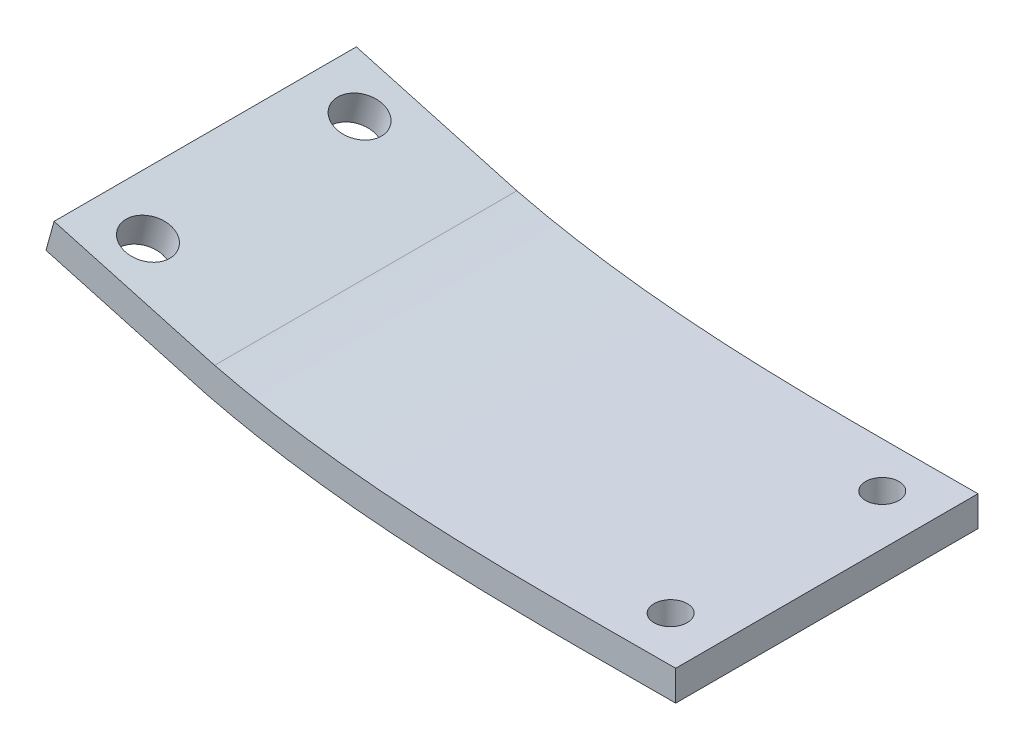
SolidWorks part; units mm, degrees
ref_plane "Piano frontale" through (0, 0, 0) normal (0, 0, 1) x (1, 0, 0)
ref_plane "Piano superiore" through (0, 0, 0) normal (0, 1, 0) x (1, 0, 0)
ref_plane "Piano destro" through (0, 0, 0) normal (1, 0, 0) x (0, 0, -1)
sketch "Schizzo1" plane through (0, 0, 0) normal (0, 0, 1) x (1, 0, 0)
  line L0 (0, 0) -> (150, 0)
  line L1 (150, 0) -> (94.2149, 0.9737) construction
  line L2 (150, 0) -> (78.851, 2.4846) construction
  line L3 (150, 0) -> (66.9131, 4.3544) construction
  line L4 (150, 0) -> (56.9541, 6.5064) construction
  line L5 (150, 0) -> (25.0148, 15.3463) construction
  line L6 (-299.0536, -537.5076) -> (-1111.2465, -622.8725) construction
  line L7 (25.0148, 15.3463) -> (56.9541, 6.5064)
  line L8 (26.6152, 21.1289) -> (58.4735, 12.3114)
  line L9 (149.9926, 6) -> (150, 0)
  line L10 (25.0148, 15.3463) -> (26.6152, 21.1289)
  spline S0 degree 3 poles (150, 0) (126.3707, -0.029) (94.9081, -0.7051) (64.164, 4.725) (56.9541, 6.5064) knots 0 0 0 0 0.761804 1 1 1 1
  spline S1 degree 1 poles (149.9926, 6) (58.4735, 12.3114) knots 0 0 1 1 construction
  spline S2 degree 3 poles (58.4735, 12.3114) (62.1265, 11.4109) (69.481, 9.8709) (84.4753, 7.647) (103.508, 6.2193) (126.6665, 5.8672) (142.2274, 5.9905) (149.9926, 6) knots 0 0 0 0 0.124885 0.249771 0.499542 0.749313 0.999084 0.999084 0.999084 0.999084
  dimension "D1" = 150
  dimension "D2" = 1
  dimension "D3" = 1
  dimension "D4" = 1
  dimension "D5" = 1
  dimension "D6" = 3
  dimension "D7" = 10.1888
  dimension "D8" = 12.0835
  dimension "D9" = 15.438
  dimension "D10" = 6
extrude "Estrusione-Estrusione1" add sketch "Schizzo1" against normal blind 60 contours S0 L7 L10 L8 S2 L9
ref_plane "Piano1" through (0, 6, 0) normal (0, 1, 0) x (1, 0, 0)
sketch "Schizzo2" plane through (0, 6, 0) normal (0, 1, 0) x (1, 0, 0)
  line L0 (139.9926, 69.5854) -> (139.9926, -19.791) construction
  line L1 (5.6305, 51) -> (178.662, 51) construction
  line L2 (149.9926, 60) -> (58.4735, 60) construction
  line L3 (149.9926, 60) -> (149.9926, 0) construction
  line L4 (149.9926, 30) -> (10.5787, 30) construction
  circle A0 centre (139.9926, 51) radius 3.3
  circle A1 centre (139.9926, 9) radius 3.3
  dimension "D3" = 6.6
  dimension "D1" = 9
  dimension "D2" = 10
extrude "Taglio-Estrusione1" cut sketch "Schizzo2" against normal through all
sketch "Schizzo3" plane through (7.3255, 26.4677, 0) normal (0.2667, 0.9638, 0) x (0.9638, -0.2667, 0)
  line L0 (30.0149, 64.9395) -> (30.0149, -8.2062) construction
  line L1 (13.2253, 51) -> (39.3589, 51) construction
  line L2 (20.0149, 60) -> (20.0149, 0) construction
  line L3 (20.0149, 60) -> (53.0709, 60) construction
  line L4 (20.0149, 30) -> (79.9795, 30) construction
  circle A0 centre (30.0149, 51) radius 4.5
  circle A1 centre (30.0149, 9) radius 4.5
  dimension "D1" = 9
  dimension "D2" = 10
  dimension "D3" = 9
extrude "Taglio-Estrusione2" cut sketch "Schizzo3" against normal through all
